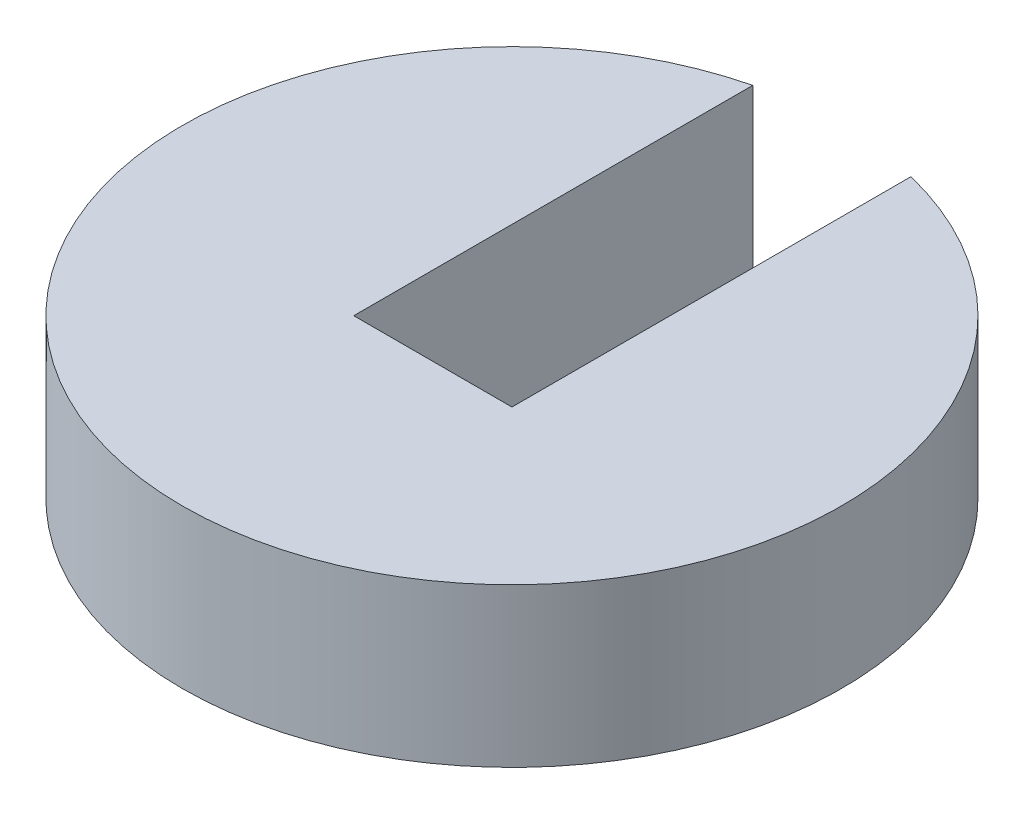
SolidWorks part; units mm, degrees
ref_plane "Plano frontal" through (0, 0, 0) normal (0, 0, 1) x (1, 0, 0)
ref_plane "Plano superior" through (0, 0, 0) normal (0, 1, 0) x (1, 0, 0)
ref_plane "Plano direito" through (0, 0, 0) normal (1, 0, 0) x (0, 0, -1)
sketch "Esboço1" plane through (0, 0, 0) normal (0, 1, 0) x (1, 0, 0)
  line L0 (-3, 12.1347) -> (-3, -3)
  line L1 (-3, -3) -> (3, -3)
  line L2 (3, -3) -> (3, 12.1347)
  arc A0 (-3, 12.1347) -> (3, 12.1347) centre (0, 0) ccw
  dimension "D1" = 25
  dimension "D2" = 6
  dimension "D3" = 3
  dimension "D4" = 3
  dimension "D5" = 15.1347
extrude "Ressalto-extrusão1" add sketch "Esboço1" along normal blind 6
